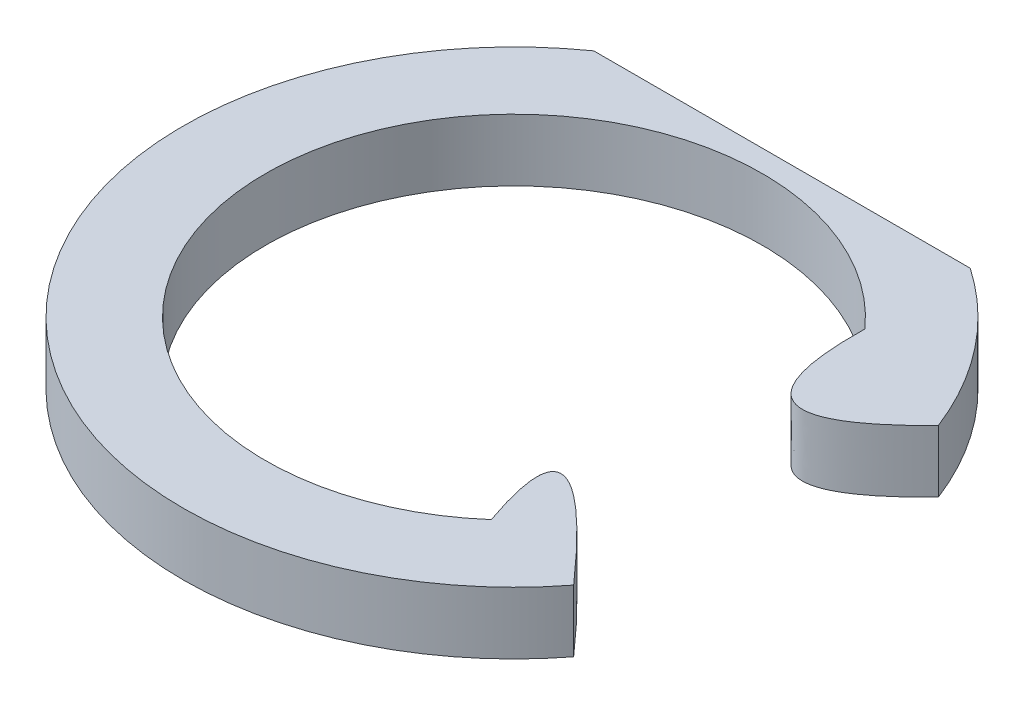
SolidWorks part; units mm, degrees
ref_plane "Front Plane" through (0, 0, 0) normal (0, 0, 1) x (1, 0, 0)
ref_plane "Top Plane" through (0, 0, 0) normal (0, 1, 0) x (1, 0, 0)
ref_plane "Right Plane" through (0, 0, 0) normal (1, 0, 0) x (0, 0, -1)
sketch "Sketch2" plane through (0, 0, 0) normal (0, 1, 0) x (1, 0, 0)
  line L3 (-10.7395, 15.2348) -> (10.4646, 15.2348)
  arc A0 (9.2411, -10.5167) -> (10.4646, 9.3001) centre (0, 0) cw
  arc A1 (14.7536, -11.3916) -> (-10.7395, 15.2348) centre (0, 0) cw
  arc A2 (10.4646, 15.2348) -> (17.2376, 6.6689) centre (0, 0) cw
  spline S0 degree 2 poles (10.4646, 9.3001) (10.2692, -0.5341) (17.2376, 6.6689) knots 0 0 0 1 1 1
  spline S1 degree 2 poles (9.2411, -10.5167) (6.1732, -1.69) (14.7536, -11.3916) knots 0 0 0 1 1 1
extrude "Boss-Extrude6" add sketch "Sketch2" against normal mid plane 3.5 contours A0 S0 A2 L3 A1 S1
